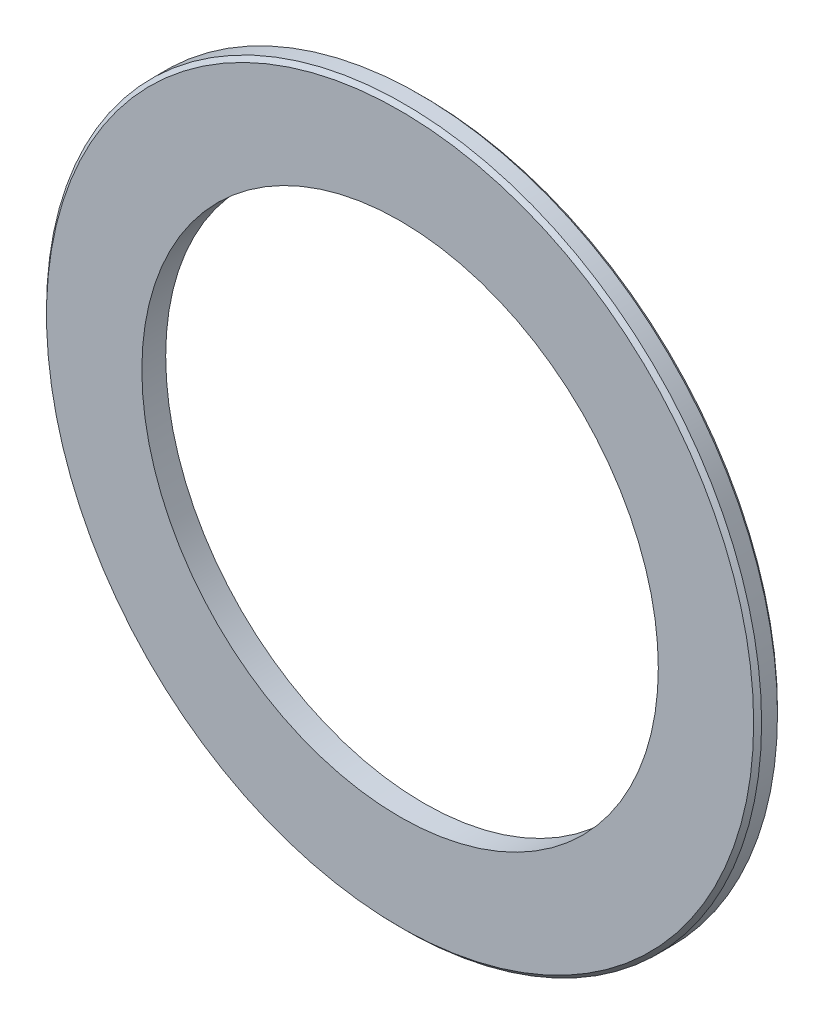
SolidWorks part; units mm, degrees
material "AISI 304"
ref_plane "Спереди" through (0, 0, 0) normal (0, 0, 1) x (1, 0, 0)
ref_plane "Сверху" through (0, 0, 0) normal (0, 1, 0) x (1, 0, 0)
ref_plane "Справа" through (0, 0, 0) normal (1, 0, 0) x (0, 0, -1)
sketch "Эскиз1" plane through (0, 0, 0) normal (0, 0, 1) x (1, 0, 0)
  circle A0 centre (0, 0) radius 45
  circle A1 centre (0, 0) radius 32.5
  dimension "D1" = 90
  dimension "65" = 65
extrude "Бобышка-Вытянуть1" add sketch "Эскиз1" along normal blind 3
chamfer "Фаска1" distance 0.5 angle 45 2 edges at (45, 0, 0) (45, 0, 3)
